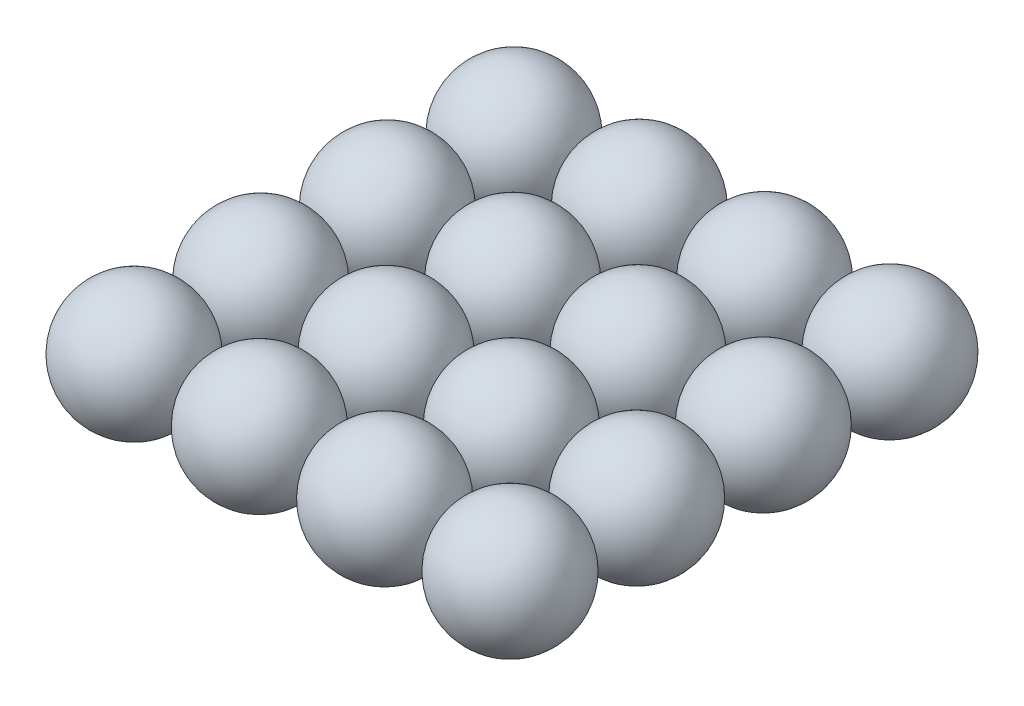
SolidWorks part; units mm, degrees
ref_plane "Front Plane" through (0, 0, 0) normal (0, 0, 1) x (1, 0, 0)
ref_plane "Top Plane" through (0, 0, 0) normal (0, 1, 0) x (1, 0, 0)
ref_plane "Right Plane" through (0, 0, 0) normal (1, 0, 0) x (0, 0, -1)
sketch "Sketch1" plane through (0, 0, 0) normal (0, 0, 1) x (1, 0, 0)
  line L0 (0, 95) -> (0, -95)
  arc A0 (0, 95) -> (0, -95) centre (0, 0) ccw
  dimension "D2" = 95
  dimension "D1" = 190
revolve "Revolve1" add sketch "Sketch1" angle 360 about L0
sketch "Sketch2" plane through (0, 0, 0) normal (0, 1, 0) x (1, 0, 0)
  line L0 (0, 0) -> (0, 573) construction
  line L1 (0, 0) -> (573, 0) construction
  dimension "D1" = 573
  dimension "D2" = 573
pattern_linear "LPattern6" count 4 spacing 193 along (0, 0, -1) of "Revolve1"
pattern_linear "LPattern7" count 4 spacing 191 along (1, 0, 0) of bodies 105 104 103 101
